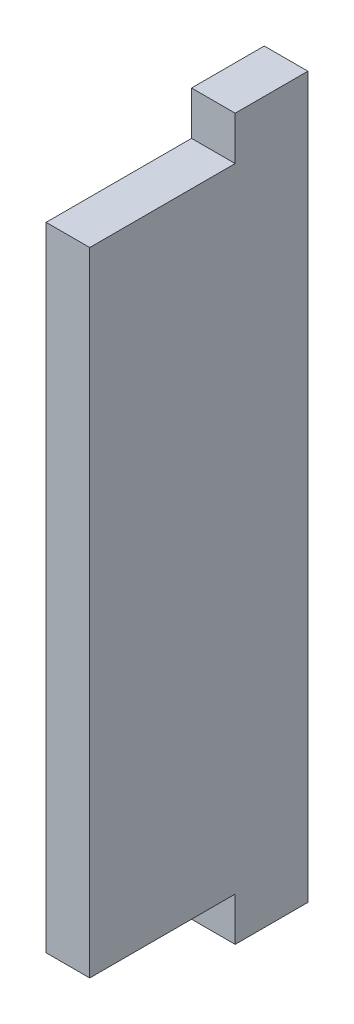
SolidWorks part; units mm, degrees
ref_plane "Front Plane" through (0, 0, 0) normal (0, 0, 1) x (1, 0, 0)
ref_plane "Top Plane" through (0, 0, 0) normal (0, 1, 0) x (1, 0, 0)
ref_plane "Right Plane" through (0, 0, 0) normal (1, 0, 0) x (0, 0, -1)
sketch "Sketch1" plane through (0, 0, 0) normal (1, 0, 0) x (0, 0, -1)
  line L0 (0, 24.75) -> (0, -24.75) construction
  line L1 (-7.5, -24.75) -> (7.5, -24.75)
  line L2 (-7.5, -24.75) -> (-7.5, 24.75)
  line L3 (-7.5, 24.75) -> (7.5, 24.75)
  line L4 (7.5, -24.75) -> (7.5, 24.75)
  dimension "D1" = 49.5
  dimension "D2" = 15
extrude "Boss-Extrude1" add sketch "Sketch1" along normal blind 3
sketch "Sketch2" plane through (3, 0, 0) normal (1, 0, 0) x (0, 0, -1)
  line L0 (7.5, -24.75) -> (7.5, 24.75) construction
  line L1 (-7.5, 24.75) -> (2.5, 24.75)
  line L2 (-7.5, 24.75) -> (-7.5, 21.75)
  line L3 (-7.5, 21.75) -> (2.5, 21.75)
  line L4 (2.5, 24.75) -> (2.5, 21.75)
  line L5 (-7.5, -24.75) -> (2.5, -24.75)
  line L6 (-7.5, -24.75) -> (-7.5, -21.75)
  line L7 (-7.5, -21.75) -> (2.5, -21.75)
  line L8 (2.5, -24.75) -> (2.5, -21.75)
  dimension "D1" = 5
  dimension "D2" = 3
extrude "Cut-Extrude1" cut sketch "Sketch2" against normal through all
